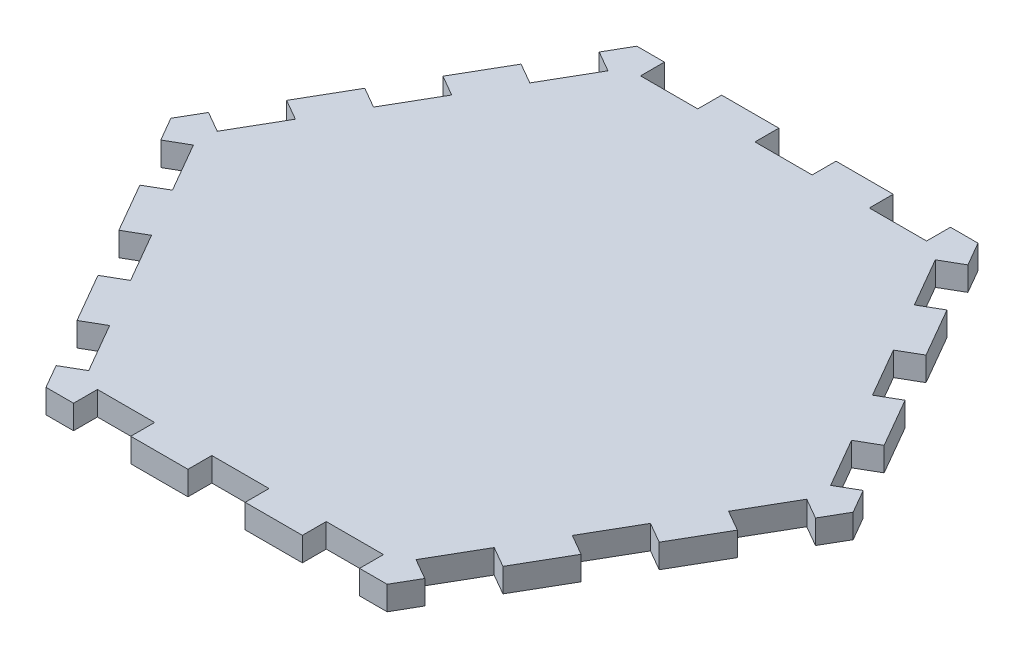
SolidWorks part; units mm, degrees
ref_plane "Front Plane" through (0, 0, 0) normal (0, 0, 1) x (1, 0, 0)
ref_plane "Top Plane" through (0, 0, 0) normal (0, 1, 0) x (1, 0, 0)
ref_plane "Right Plane" through (0, 0, 0) normal (1, 0, 0) x (0, 0, -1)
sketch "Sketch1" plane through (0, 0, 0) normal (0, 1, 0) x (1, 0, 0)
  line L0 (-22.87, -39.612) -> (-19.175, -39.612)
  line L13 (-19.175, -39.612) -> (-19.175, -36.412)
  line L14 (-19.175, -36.412) -> (-11.505, -36.412)
  line L15 (-11.505, -36.412) -> (-11.505, -39.612)
  line L16 (-11.505, -39.612) -> (-3.835, -39.612)
  line L17 (-3.835, -39.612) -> (-3.835, -36.412)
  line L18 (-3.835, -36.412) -> (3.835, -36.412)
  line L19 (3.835, -36.412) -> (3.835, -39.612)
  line L21 (-45.74, 0) -> (-43.8925, -3.2)
  line L22 (3.835, -39.612) -> (11.505, -39.612)
  line L23 (11.505, -39.612) -> (11.505, -36.412)
  line L24 (11.505, -36.412) -> (19.175, -36.412)
  line L25 (19.175, -36.412) -> (19.175, -39.612)
  line L26 (19.175, -39.612) -> (22.87, -39.612)
  line L27 (22.87, -39.612) -> (24.7175, -36.412)
  line L28 (45.74, 0) -> (22.87, 39.612) construction
  line L29 (24.7175, -36.412) -> (21.9462, -34.812)
  line L30 (21.9462, -34.812) -> (25.7812, -28.1696)
  line L31 (25.7812, -28.1696) -> (28.5525, -29.7696)
  line L32 (28.5525, -29.7696) -> (32.3875, -23.1272)
  line L33 (32.3875, -23.1272) -> (29.6162, -21.5272)
  line L34 (29.6162, -21.5272) -> (33.4512, -14.8848)
  line L35 (33.4512, -14.8848) -> (36.2225, -16.4848)
  line L36 (36.2225, -16.4848) -> (40.0575, -9.8424)
  line L37 (40.0575, -9.8424) -> (37.2862, -8.2424)
  line L38 (37.2862, -8.2424) -> (41.1212, -1.6)
  line L39 (41.1212, -1.6) -> (43.8925, -3.2)
  line L40 (43.8925, -3.2) -> (45.74, 0)
  line L41 (45.74, 0) -> (43.8925, 3.2)
  line L42 (22.87, 39.612) -> (-22.87, 39.612) construction
  line L43 (-22.87, 39.612) -> (-45.74, 0) construction
  line L44 (43.8925, 3.2) -> (41.1212, 1.6)
  line L45 (41.1212, 1.6) -> (37.2862, 8.2424)
  line L46 (37.2862, 8.2424) -> (40.0575, 9.8424)
  line L47 (40.0575, 9.8424) -> (36.2225, 16.4848)
  line L48 (36.2225, 16.4848) -> (33.4512, 14.8848)
  line L49 (33.4512, 14.8848) -> (29.6162, 21.5272)
  line L50 (29.6162, 21.5272) -> (32.3875, 23.1272)
  line L51 (32.3875, 23.1272) -> (28.5525, 29.7696)
  line L52 (28.5525, 29.7696) -> (25.7812, 28.1696)
  line L53 (25.7812, 28.1696) -> (21.9462, 34.812)
  line L54 (21.9462, 34.812) -> (24.7175, 36.412)
  line L55 (24.7175, 36.412) -> (22.87, 39.612)
  line L56 (22.87, 39.612) -> (19.175, 39.612)
  line L57 (-45.74, 0) -> (-22.87, -39.612) construction
  line L58 (-22.87, -39.612) -> (22.87, -39.612) construction
  line L59 (19.175, 39.612) -> (19.175, 36.412)
  line L60 (19.175, 36.412) -> (11.505, 36.412)
  line L61 (11.505, 36.412) -> (11.505, 39.612)
  line L62 (11.505, 39.612) -> (3.835, 39.612)
  line L63 (3.835, 39.612) -> (3.835, 36.412)
  line L64 (3.835, 36.412) -> (-3.835, 36.412)
  line L65 (-3.835, 36.412) -> (-3.835, 39.612)
  line L66 (-3.835, 39.612) -> (-11.505, 39.612)
  line L67 (-11.505, 39.612) -> (-11.505, 36.412)
  line L68 (-11.505, 36.412) -> (-19.175, 36.412)
  line L69 (-19.175, 36.412) -> (-19.175, 39.612)
  line L70 (-19.175, 39.612) -> (-22.87, 39.612)
  line L71 (-22.87, 39.612) -> (-24.7175, 36.412)
  line L72 (22.87, -39.612) -> (45.74, 0) construction
  line L73 (-43.8925, -3.2) -> (-41.1212, -1.6)
  line L74 (-24.7175, 36.412) -> (-21.9462, 34.812)
  line L75 (-21.9462, 34.812) -> (-25.7812, 28.1696)
  line L76 (-25.7812, 28.1696) -> (-28.5525, 29.7696)
  line L77 (-28.5525, 29.7696) -> (-32.3875, 23.1272)
  line L78 (-32.3875, 23.1272) -> (-29.6162, 21.5272)
  line L79 (-29.6162, 21.5272) -> (-33.4512, 14.8848)
  line L80 (-33.4512, 14.8848) -> (-36.2225, 16.4848)
  line L81 (-36.2225, 16.4848) -> (-40.0575, 9.8424)
  line L82 (-40.0575, 9.8424) -> (-37.2862, 8.2424)
  line L83 (-37.2862, 8.2424) -> (-41.1212, 1.6)
  line L84 (-41.1212, 1.6) -> (-43.8925, 3.2)
  line L85 (-43.8925, 3.2) -> (-45.74, 0)
  line L86 (-41.1212, -1.6) -> (-37.2862, -8.2424)
  line L87 (-37.2862, -8.2424) -> (-40.0575, -9.8424)
  line L88 (-40.0575, -9.8424) -> (-36.2225, -16.4848)
  line L89 (-36.2225, -16.4848) -> (-33.4512, -14.8848)
  line L90 (-33.4512, -14.8848) -> (-29.6162, -21.5272)
  line L91 (-29.6162, -21.5272) -> (-32.3875, -23.1272)
  line L92 (-32.3875, -23.1272) -> (-28.5525, -29.7696)
  line L93 (-28.5525, -29.7696) -> (-25.7812, -28.1696)
  line L94 (-25.7812, -28.1696) -> (-21.9462, -34.812)
  line L95 (-21.9462, -34.812) -> (-24.7175, -36.412)
  line L96 (-24.7175, -36.412) -> (-22.87, -39.612)
  line L97 (-21.9462, -34.812) -> (-19.175, -39.612) construction
  line L102 (19.175, -36.412) -> (24.7175, -36.412) construction
  line L103 (-19.175, -36.412) -> (-24.7175, -36.412) construction
  line L126 (21.9462, -34.812) -> (19.175, -39.612) construction
  circle A0 centre (0, 0) radius 39.612 construction
  dimension "D9" = 79.224
  dimension "D79" = 3.2
  dimension "D10" = 38.3499
  dimension "D12" = 120
  dimension "D2" = 3.695
  dimension "D3" = 7.67
  dimension "D5" = 38.3499
  dimension "D14" = 5.5426
extrude "Boss-Extrude3" add sketch "Sketch1" along normal blind 3.2
equation "\"Thick\"=3.2"
equation "\"D79@Sketch1\"=\"Thick\""
equation "\"D10@Sketch1\"=\"D5@Sketch1\""
equation "\"angletabwidth\"=4"
